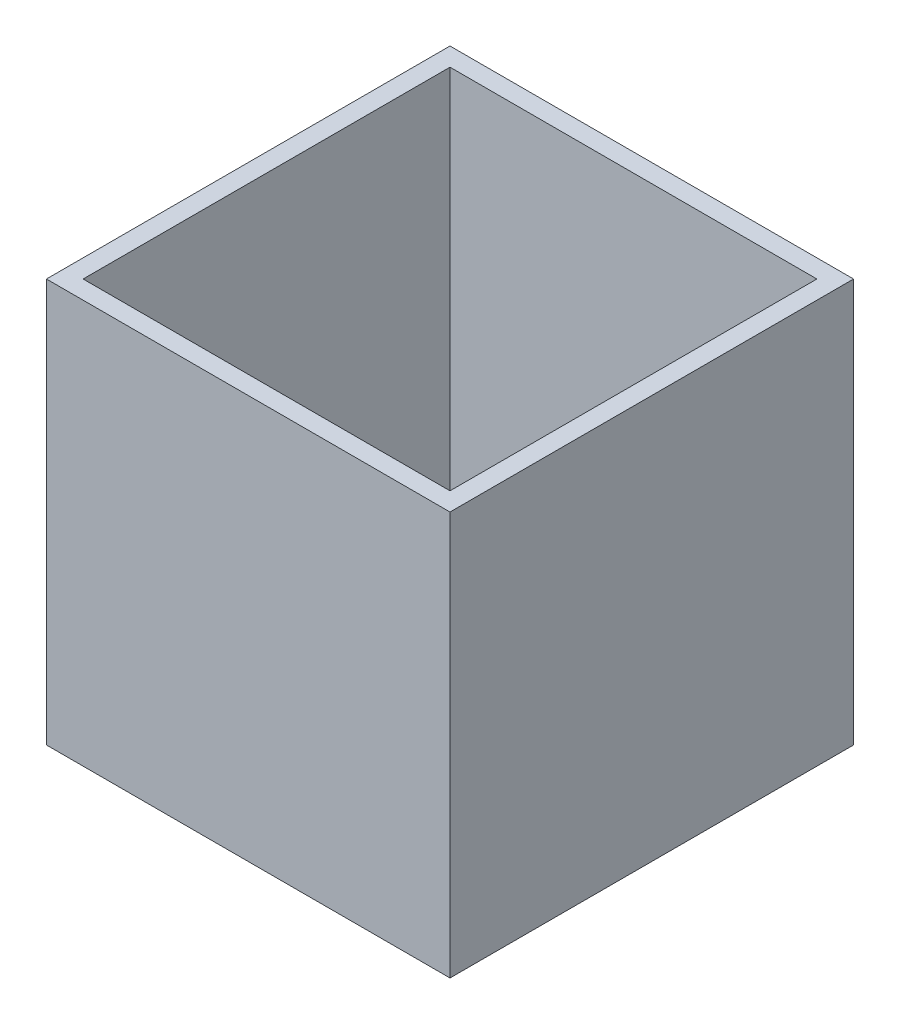
SolidWorks part; units mm, degrees
material "PVC 0.007 Plasticized"
ref_plane "Front Plane" through (0, 0, 0) normal (0, 0, 1) x (1, 0, 0)
ref_plane "Top Plane" through (0, 0, 0) normal (0, 1, 0) x (1, 0, 0)
ref_plane "Right Plane" through (0, 0, 0) normal (1, 0, 0) x (0, 0, -1)
sketch "Sketch1" plane through (0, 0, 0) normal (1, 0, 0) x (0, 0, -1)
  line L1 (-27.94, -27.94) -> (27.94, -27.94)
  line L2 (-27.94, -27.94) -> (-27.94, 27.94)
  line L3 (-27.94, 27.94) -> (27.94, 27.94)
  line L4 (27.94, -27.94) -> (27.94, 27.94)
  line L5 (-27.94, -27.94) -> (27.94, 27.94) construction
  line L6 (-27.94, 27.94) -> (27.94, -27.94) construction
  point P0 (0, 0)
  dimension "D1" = 55.88
  dimension "D2" = 55.88
extrude "Boss-Extrude1" add sketch "Sketch1" along normal blind 55.88
shell "Shell1" thickness 2.54
